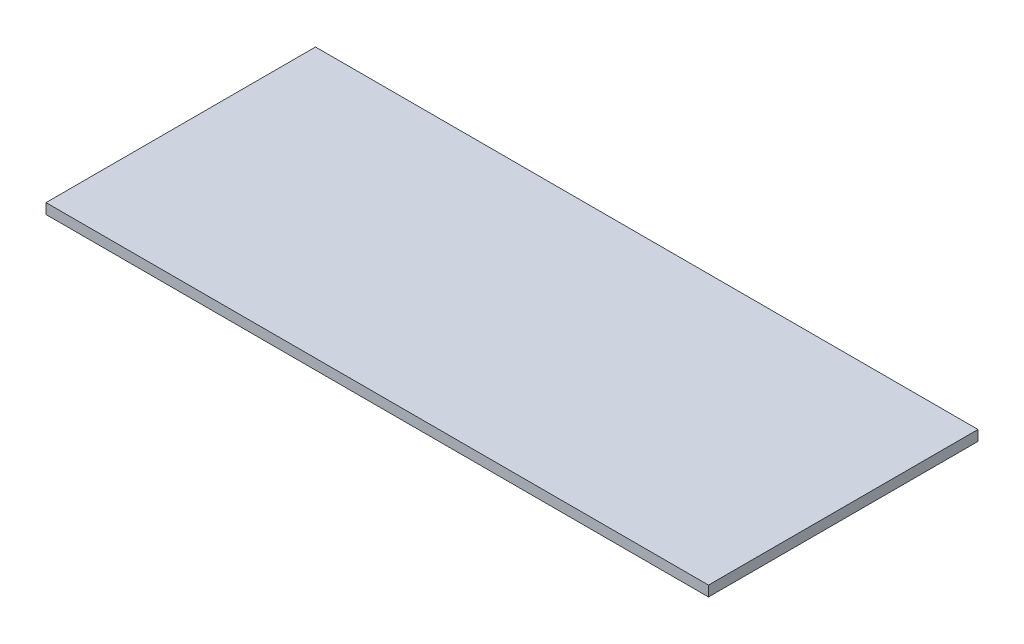
SolidWorks part; units mm, degrees
ref_plane "Front Plane" through (0, 0, 0) normal (0, 0, 1) x (1, 0, 0)
ref_plane "Top Plane" through (0, 0, 0) normal (0, 1, 0) x (1, 0, 0)
ref_plane "Right Plane" through (0, 0, 0) normal (1, 0, 0) x (0, 0, -1)
sketch "Sketch1" plane through (0, 0, 0) normal (0, 1, 0) x (1, 0, 0)
  line L1 (-59.1289, 95.5995) -> (245.6711, 95.5995)
  line L2 (-59.1289, 95.5995) -> (-59.1289, -28.4005)
  line L3 (-59.1289, -28.4005) -> (245.6711, -28.4005)
  line L4 (245.6711, 95.5995) -> (245.6711, -28.4005)
  dimension "D1" = 304.8
  dimension "D2" = 124
extrude "Boss-Extrude2" add sketch "Sketch1" along normal blind 4.7625
